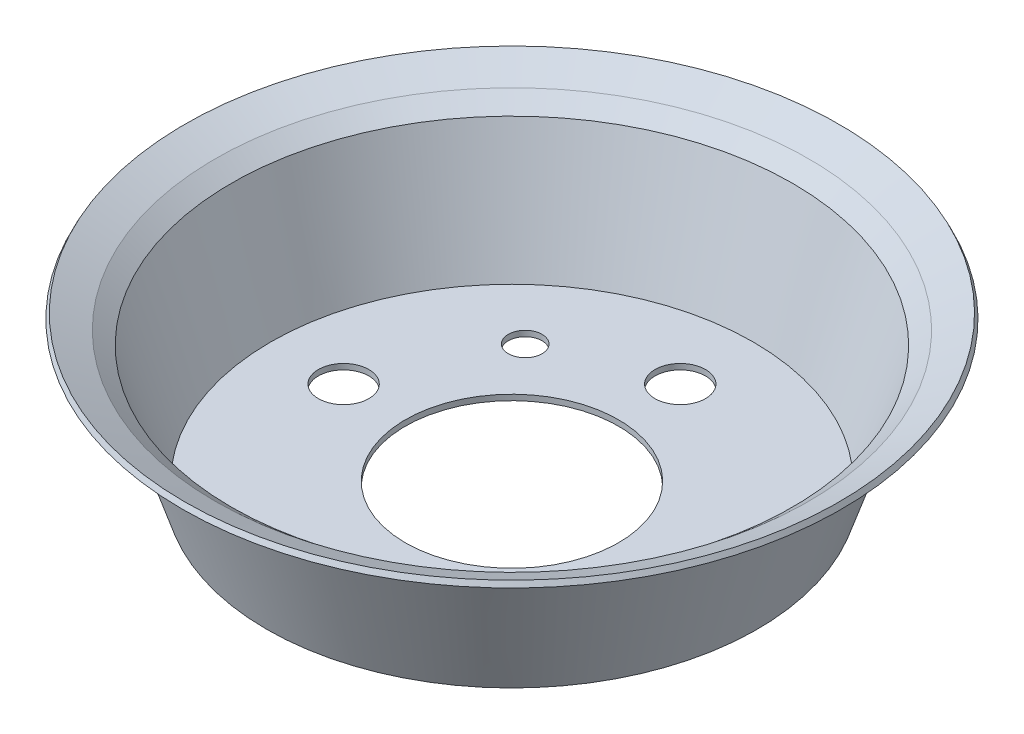
SolidWorks part; units mm, degrees
ref_plane "Спереди" through (0, 0, 0) normal (0, 0, 1) x (1, 0, 0)
ref_plane "Сверху" through (0, 0, 0) normal (0, 1, 0) x (1, 0, 0)
ref_plane "Справа" through (0, 0, 0) normal (1, 0, 0) x (0, 0, -1)
sketch "Эскиз1" plane through (0, 0, 0) normal (0, 0, 1) x (1, 0, 0)
  line L0 (0, 0) -> (0, -32.1034) construction
  line L1 (-5.6001, 0) -> (69.589, 0) construction
  line L2 (19, 0) -> (43, 0)
  line L3 (52.8896, 23.3322) -> (58.3028, 25.953)
  line L4 (50, 21) -> (43, 0)
  line L5 (50, 21) -> (52.8896, 23.3322)
revolve "Повернуть-Тонкостенный1" add sketch "Эскиз1" angle 360 about L0
sketch "Эскиз2" plane through (0, 0, 0) normal (0, 1, 0) x (1, 0, 0)
  line L0 (-12.04, 0) -> (79.8729, 0) construction
  line L1 (0, 1.1092) -> (0, -37.1354) construction
  line L2 (19, 0) -> (19, -28.0145) construction
  line L3 (0, 19) -> (26.2597, 19) construction
  circle A0 centre (30, 0) radius 4.5
  circle A1 centre (-30, 0) radius 4.5
  circle A3 centre (0, 30) radius 4.5
  circle A4 centre (0, -30) radius 4.5
  dimension "D1" = 11
  dimension "D2" = 11
  dimension "D3" = 9
  dimension "D4" = 9
  dimension "D5" = 30
extrude "Вытянуть1" cut sketch "Эскиз2" against normal mid plane 80
sketch "Эскиз3" plane through (0, 0, 0) normal (0, 1, 0) x (1, 0, 0)
  line L0 (0, 0) -> (90.3743, 0) construction
  line L1 (0, 0) -> (0, -12.7643) construction
  circle A0 centre (0, 0) radius 27.2297 construction
  circle A1 centre (20, -22.3607) radius 3
  circle A2 centre (-20, 22.3607) radius 3
  dimension "D1" = 6
  dimension "D5" = 54.4594
  dimension "D2" = 6
extrude "Вытянуть2" cut sketch "Эскиз3" against normal mid plane 10
